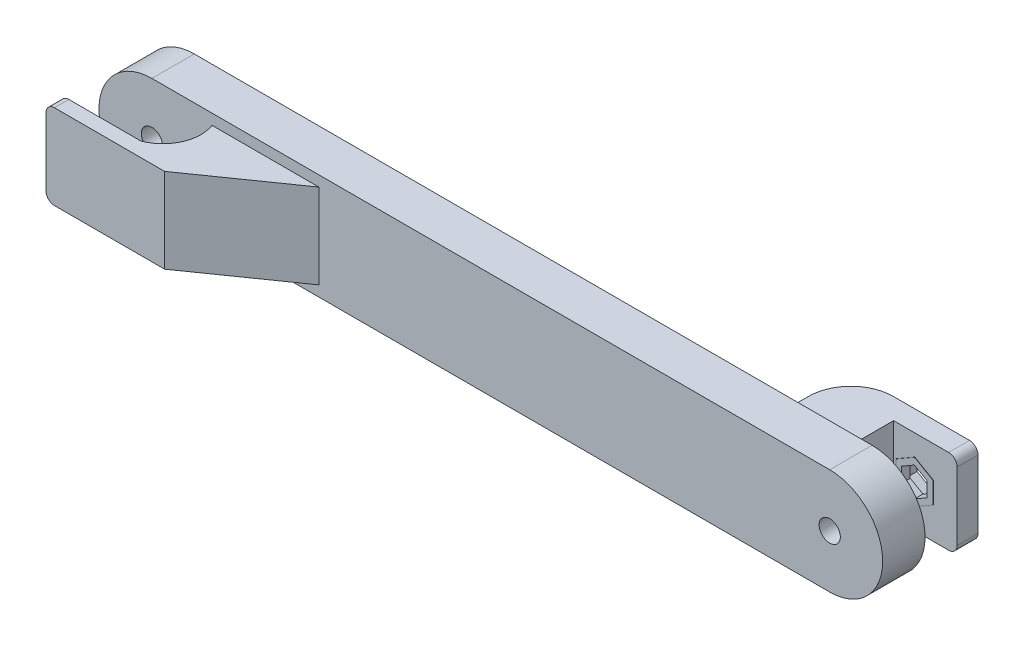
SolidWorks part; units mm, degrees
ref_plane "Front" through (0, 0, 0) normal (0, 0, 1) x (1, 0, 0)
ref_plane "Top" through (0, 0, 0) normal (0, 1, 0) x (1, 0, 0)
ref_plane "Right" through (0, 0, 0) normal (1, 0, 0) x (0, 0, -1)
sketch "Sketch1" plane through (0, 0, 0) normal (0, 0, 1) x (1, 0, 0)
  line L0 (299.8703, -79.0606) -> (503.0703, -79.0606) construction
  line L1 (299.8703, -63.1856) -> (503.0703, -63.1856)
  line L2 (299.8703, -94.9356) -> (503.0703, -94.9356)
  line L3 (401.4703, -94.9356) -> (401.4703, -63.1856) construction
  arc A0 (299.8703, -63.1856) -> (299.8703, -94.9356) centre (299.8703, -79.0606) ccw
  arc A1 (503.0703, -94.9356) -> (503.0703, -63.1856) centre (503.0703, -79.0606) ccw
  circle A2 centre (299.8703, -79.0606) radius 3.175
  circle A3 centre (503.0703, -79.0606) radius 3.175
  point P2 (401.4703, -79.0606)
  dimension "D1" = 203.2
  dimension "D2" = 15.875
  dimension "D3" = 31.75
extrude "Boss-Extrude1" add sketch "Sketch1" along normal blind 12.7
sketch "Sketch2" plane through (0, 0, 0) normal (0, 0, -1) x (-1, 0, 0)
  line L5 (-477.6703, -66.3606) -> (-477.6703, -91.7606)
  line L6 (-513.2303, -91.7606) -> (-477.6703, -91.7606)
  line L7 (-515.7703, -89.2206) -> (-515.7703, -68.9006)
  line L8 (-513.2303, -66.3606) -> (-477.6703, -66.3606)
  line L10 (-515.7703, -91.7606) -> (-490.3703, -66.3606) construction
  line L11 (-515.7703, -66.3606) -> (-490.3703, -91.7606) construction
  line L19 (-503.0703, -72.6448) -> (-508.6265, -75.8527)
  line L20 (-508.6265, -75.8527) -> (-508.6265, -82.2685)
  line L21 (-508.6265, -82.2685) -> (-503.0703, -85.4764)
  line L22 (-503.0703, -85.4764) -> (-497.514, -82.2685)
  line L23 (-497.514, -82.2685) -> (-497.514, -75.8527)
  line L24 (-497.514, -75.8527) -> (-503.0703, -72.6448)
  arc A0 (-513.2303, -91.7606) -> (-515.7703, -89.2206) centre (-513.2303, -89.2206) cw
  arc A3 (-515.7703, -68.9006) -> (-513.2303, -66.3606) centre (-513.2303, -68.9006) cw
  circle A4 centre (-503.0703, -79.0606) radius 5.5562 construction
  point P0 (-503.0703, -79.0606)
  dimension "D3" = 2.54
  dimension "D1" = 25.4
  dimension "D2" = 25.4
  dimension "D4" = 35.56
ref_plane "Plane5" through (401.447, 0, 0) normal (1, 0, 0) x (0, 0, -1)
surface "Surface-MidSurface2" parameters "D0"=50000
sketch "Sketch7" plane through (0, 0, 12.7) normal (0, 0, 1) x (1, 0, 0)
  line L0 (310.0303, -66.3606) -> (312.5703, -66.3606)
  line L1 (289.7103, -91.7606) -> (310.0303, -91.7606)
  line L2 (287.1703, -89.2206) -> (287.1703, -68.9006)
  line L3 (289.7103, -66.3606) -> (310.0303, -66.3606)
  line L5 (287.1703, -91.7606) -> (312.5703, -66.3606) construction
  line L6 (287.1703, -66.3606) -> (312.5703, -91.7606) construction
  line L7 (312.5703, -66.3606) -> (322.7303, -66.3606)
  line L8 (322.7303, -66.3606) -> (322.7303, -91.7606)
  line L9 (310.0303, -91.7606) -> (322.7303, -91.7606)
  arc A0 (289.7103, -91.7606) -> (287.1703, -89.2206) centre (289.7103, -89.2206) cw
  arc A3 (287.1703, -68.9006) -> (289.7103, -66.3606) centre (289.7103, -68.9006) cw
  point P0 (299.8703, -79.0606)
  dimension "D3" = 2.54
  dimension "D1" = 25.4
  dimension "D2" = 25.4
  dimension "D4" = 10.16
extrude "Boss-Extrude8" add sketch "Sketch7" along normal blind 19.05
sketch "Sketch8" plane through (0, -66.3606, 0) normal (0, 1, 0) x (1, 0, 0)
  line L0 (287.1703, -12.7) -> (317.9043, -12.7)
  line L1 (503.0703, -12.7) -> (299.8703, -12.7) construction
  line L2 (287.1703, -12.7) -> (287.1703, -27.432)
  line L3 (287.1703, -31.75) -> (287.1703, -12.7) construction
  line L4 (287.1703, -27.432) -> (311.3003, -27.432)
  arc A0 (317.9043, -12.7) -> (311.3003, -27.432) centre (307.218, -16.7558) cw
  dimension "D1" = 30.734
  dimension "D2" = 14.732
  dimension "D3" = 24.13
extrude "Cut-Extrude3" cut sketch "Sketch8" against normal blind 41.148
sketch "Sketch9" plane through (0, -66.3606, 0) normal (0, 1, 0) x (1, 0, 0)
  line L0 (322.7303, -31.75) -> (349.9365, -12.7)
  line L1 (503.0703, -12.7) -> (299.8703, -12.7) construction
  line L4 (322.7303, -12.7) -> (349.9365, -12.7)
  line L5 (322.7303, -31.75) -> (322.7303, -12.7)
  dimension "D1" = 35
extrude "Boss-Extrude9" add sketch "Sketch9" against normal blind 25.4
extrude "Boss-Extrude11" add sketch "Sketch2" along normal blind 19.05
sketch "Sketch10" plane through (0, -91.7606, 0) normal (0, -1, 0) x (1, 0, 0)
  line L1 (515.7703, 0) -> (515.7703, -12.7946)
  line L2 (515.7703, -19.05) -> (515.7703, 0) construction
  line L3 (515.7703, -12.7946) -> (496.7203, -12.7946)
  line L4 (515.7703, 0) -> (496.7203, 0)
  line L5 (299.8703, 0) -> (503.0703, 0) construction
  line L9 (496.7203, 0) -> (496.7203, -12.7946)
extrude "Cut-Extrude5" cut sketch "Sketch10" against normal blind 25.4
ref_plane "Plane6" through (0, 0, -12.7) normal (0, 0, -1) x (-1, 0, 0)
sketch "Sketch11" plane through (0, 0, -12.7) normal (0, 0, -1) x (-1, 0, 0)
  line L2 (-503.0703, -72.6448) -> (-508.6265, -75.8527)
  line L3 (-508.6265, -75.8527) -> (-508.6265, -82.2685)
  line L4 (-508.6265, -82.2685) -> (-503.0703, -85.4764)
  line L5 (-503.0703, -85.4764) -> (-497.514, -82.2685)
  line L6 (-497.514, -82.2685) -> (-497.514, -75.8527)
  line L7 (-497.514, -75.8527) -> (-503.0703, -72.6448)
  line L8 (-503.0703, -74.6612) -> (-506.8803, -76.8609)
  line L9 (-506.8803, -76.8609) -> (-506.8803, -81.2603)
  line L10 (-506.8803, -81.2603) -> (-503.0703, -83.46)
  line L11 (-503.0703, -83.46) -> (-499.2603, -81.2603)
  line L12 (-499.2603, -81.2603) -> (-499.2603, -76.8609)
  line L13 (-499.2603, -76.8609) -> (-503.0703, -74.6612)
  circle A0 centre (-503.0703, -79.0606) radius 5.5562 construction
  circle A1 centre (-503.0703, -79.0606) radius 3.81 construction
extrude "Boss-Extrude12" add sketch "Sketch11" along normal blind 2.54
sketch "Sketch12" plane through (0, -66.3606, 0) normal (0, 1, 0) x (1, 0, 0)
  line L0 (477.6703, 6.35) -> (477.6703, 9.525)
  line L1 (477.6703, 19.05) -> (477.6703, 0) construction
  line L2 (490.3703, 19.05) -> (486.4903, 19.05)
  line L3 (477.6703, 19.05) -> (513.2303, 19.05) construction
  line L4 (486.4903, 19.05) -> (477.6703, 19.05)
  line L5 (477.6703, 19.05) -> (477.6703, 9.525)
  arc A0 (477.6703, 6.35) -> (490.3703, 19.05) centre (490.3703, 6.35) cw
  point P10 (477.6703, 19.05)
  dimension "D1" = 12.7
extrude "Cut-Extrude6" cut sketch "Sketch12" against normal blind 25.4 contours L5 L0 A0 L2 L4
